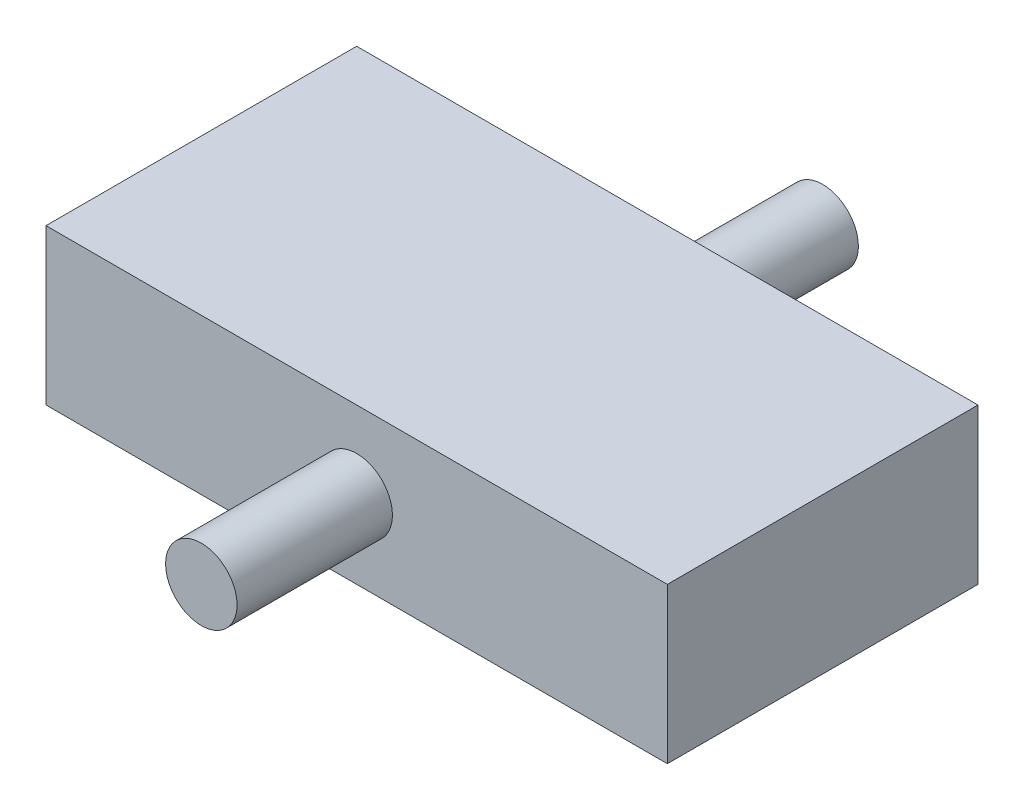
SolidWorks part; units mm, degrees
ref_plane "Front Plane" through (0, 0, 0) normal (0, 0, 1) x (1, 0, 0)
ref_plane "Top Plane" through (0, 0, 0) normal (0, 1, 0) x (1, 0, 0)
ref_plane "Right Plane" through (0, 0, 0) normal (1, 0, 0) x (0, 0, -1)
sketch "Sketch1" plane through (0, 0, 0) normal (0, 1, 0) x (1, 0, 0)
  line L1 (-50.8, -25.4) -> (50.8, -25.4)
  line L2 (-50.8, -25.4) -> (-50.8, 25.4)
  line L3 (-50.8, 25.4) -> (50.8, 25.4)
  line L4 (50.8, -25.4) -> (50.8, 25.4)
  line L5 (0, 25.4) -> (0, -25.4) construction
  line L6 (-50.8, 0) -> (50.8, 0) construction
  point P0 (0, 0)
  dimension "D1" = 101.6
  dimension "D2" = 50.8
extrude "Boss-Extrude1" add sketch "Sketch1" along normal blind 25.4
sketch "Sketch2" plane through (0, 0, 25.4) normal (0, 0, 1) x (1, 0, 0)
  circle A0 centre (0, 12.7) radius 5.842
extrude "Boss-Extrude2" add sketch "Sketch2" along normal blind 25.4
mirror "Mirror1" about plane through (0, 0, 0) normal (0, 0, 1) of "Boss-Extrude2"
